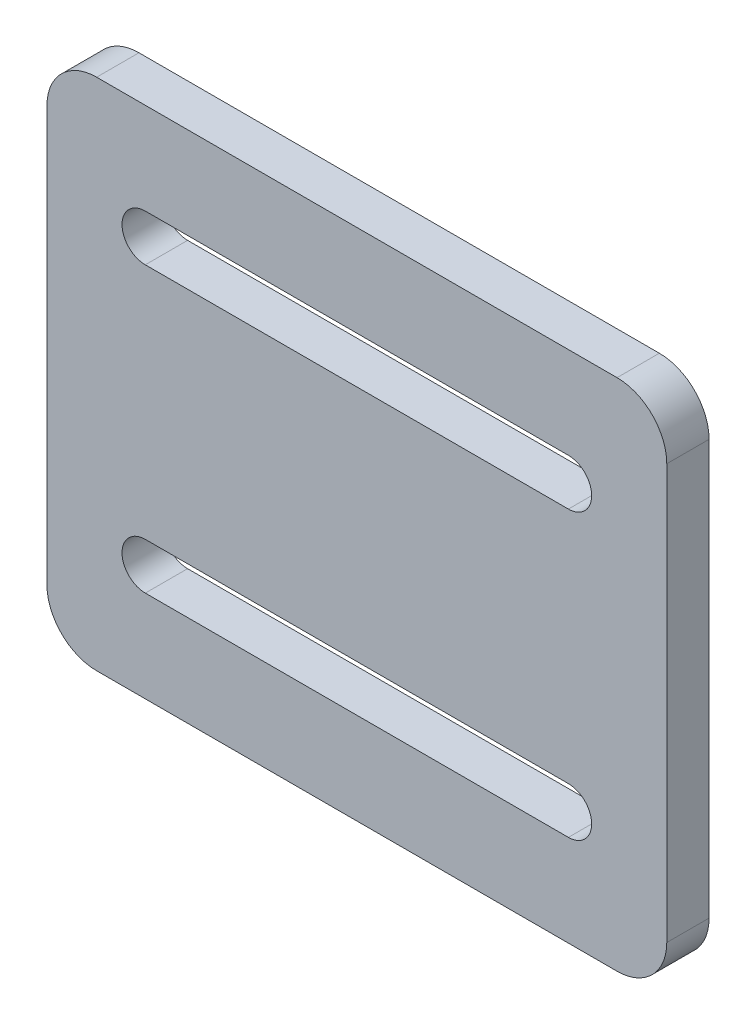
SolidWorks part; units mm, degrees
material "Thornel Mat VMA"
ref_plane "Alzado" through (0, 0, 0) normal (0, 0, 1) x (1, 0, 0)
ref_plane "Planta" through (0, 0, 0) normal (0, 1, 0) x (1, 0, 0)
ref_plane "Vista lateral" through (0, 0, 0) normal (1, 0, 0) x (0, 0, -1)
sketch "Croquis1" plane through (0, 0, 0) normal (0, 0, 1) x (1, 0, 0)
  line L8 (-39.5544, 20.8824) -> (-39.5544, 1.2824)
  line L9 (-36.8544, -1.4176) -> (-12.2544, -1.4176)
  line L10 (-9.5544, 1.2824) -> (-9.5544, 20.8824)
  line L11 (-12.2544, 23.5824) -> (-36.8544, 23.5824)
  line L12 (-14.5544, 18.9024) -> (-34.5544, 18.9024)
  line L13 (-34.5544, 3.2624) -> (-14.5544, 3.2624)
  line L14 (-14.5544, 5.4624) -> (-34.5544, 5.4624)
  line L15 (-34.5544, 16.7024) -> (-14.5544, 16.7024)
  arc A8 (-39.5544, 1.2824) -> (-36.8544, -1.4176) centre (-36.8544, 1.2824) ccw
  arc A9 (-12.2544, -1.4176) -> (-9.5544, 1.2824) centre (-12.2544, 1.2824) ccw
  arc A10 (-9.5544, 20.8824) -> (-12.2544, 23.5824) centre (-12.2544, 20.8824) ccw
  arc A11 (-36.8544, 23.5824) -> (-39.5544, 20.8824) centre (-36.8544, 20.8824) ccw
  arc A12 (-14.5544, 16.7024) -> (-14.5544, 18.9024) centre (-14.5544, 17.8024) ccw
  arc A13 (-34.5544, 18.9024) -> (-34.5544, 16.7024) centre (-34.5544, 17.8024) ccw
  arc A14 (-14.5544, 3.2624) -> (-14.5544, 5.4624) centre (-14.5544, 4.3624) ccw
  arc A15 (-34.5544, 5.4624) -> (-34.5544, 3.2624) centre (-34.5544, 4.3624) ccw
  dimension "D1" = 25
  dimension "D2" = 30
  dimension "D3" = 20
extrude "Saliente-Extruir1" add sketch "Croquis1" along normal blind 2
sketch "Croquis2" plane through (0, 0, 2) normal (0, 0, 1) x (1, 0, 0)
  line L0 (-39.2044, 20.8824) -> (-39.2044, 1.2824)
  line L1 (-36.8544, -1.0676) -> (-12.2544, -1.0676)
  line L2 (-9.9044, 1.2824) -> (-9.9044, 20.8824)
  line L3 (-12.2544, 23.2324) -> (-36.8544, 23.2324)
  line L8 (-39.5544, 20.8824) -> (-39.5544, 1.2824)
  line L9 (-36.8544, -1.4176) -> (-12.2544, -1.4176)
  line L10 (-9.5544, 1.2824) -> (-9.5544, 20.8824)
  line L11 (-12.2544, 23.5824) -> (-36.8544, 23.5824)
  line L12 (-39.5544, 20.8824) -> (-39.5544, 1.2824)
  line L13 (-36.8544, -1.4176) -> (-12.2544, -1.4176)
  line L14 (-9.5544, 1.2824) -> (-9.5544, 20.8824)
  line L15 (-12.2544, 23.5824) -> (-36.8544, 23.5824)
  arc A0 (-36.8544, 23.2324) -> (-39.2044, 20.8824) centre (-36.8544, 20.8824) ccw
  arc A1 (-39.2044, 1.2824) -> (-36.8544, -1.0676) centre (-36.8544, 1.2824) ccw
  arc A2 (-12.2544, -1.0676) -> (-9.9044, 1.2824) centre (-12.2544, 1.2824) ccw
  arc A3 (-9.9044, 20.8824) -> (-12.2544, 23.2324) centre (-12.2544, 20.8824) ccw
  arc A8 (-36.8544, 23.5824) -> (-39.5544, 20.8824) centre (-36.8544, 20.8824) ccw
  arc A9 (-39.5544, 1.2824) -> (-36.8544, -1.4176) centre (-36.8544, 1.2824) ccw
  arc A10 (-12.2544, -1.4176) -> (-9.5544, 1.2824) centre (-12.2544, 1.2824) ccw
  arc A11 (-9.5544, 20.8824) -> (-12.2544, 23.5824) centre (-12.2544, 20.8824) ccw
  arc A12 (-36.8544, 23.5824) -> (-39.5544, 20.8824) centre (-36.8544, 20.8824) ccw
  arc A13 (-39.5544, 1.2824) -> (-36.8544, -1.4176) centre (-36.8544, 1.2824) ccw
  arc A14 (-12.2544, -1.4176) -> (-9.5544, 1.2824) centre (-12.2544, 1.2824) ccw
  arc A15 (-9.5544, 20.8824) -> (-12.2544, 23.5824) centre (-12.2544, 20.8824) ccw
  dimension "D1" = 0
  dimension "D2" = 0.35
extrude "Cortar-Extruir1" cut sketch "Croquis2" against normal up to vertex (2 mm away)
